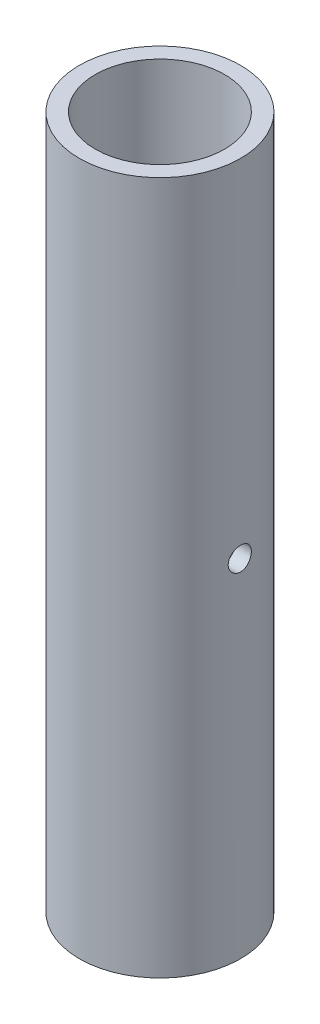
SolidWorks part; units mm, degrees
material "PVC Rigid"
ref_plane "Front Plane" through (0, 0, 0) normal (0, 0, 1) x (1, 0, 0)
ref_plane "Top Plane" through (0, 0, 0) normal (0, 1, 0) x (1, 0, 0)
ref_plane "Right Plane" through (0, 0, 0) normal (1, 0, 0) x (0, 0, -1)
sketch "Sketch2" plane through (0, 0, 0) normal (0, 1, 0) x (1, 0, 0)
  circle A0 centre (0, 0) radius 17.45
  circle A1 centre (0, 0) radius 14
  dimension "D1" = 28
  dimension "D2" = 34.9
extrude "Boss-Extrude1" add sketch "Sketch2" against normal blind 150
ref_plane "Plane1" through (17.45, 0, 0) normal (1, 0, 0) x (0, 0, -1)
hole_wizard "Tap Drill for M6x1.0 Tap1" positions "Sketch3" profile "Sketch4" hole size "M6x1.0" standard "ANSI Metric" end condition through all
sketch "Sketch3" plane through (17.45, 0, 0) normal (1, 0, 0) x (0, 0, -1)
  line L0 (14, 0) -> (-14, 0) construction
  line L1 (-17.45, 0) -> (-17.45, -150) construction
  point P0 (0, -75)
  dimension "D1" = 75
  dimension "D2" = 17.45
sketch "Sketch4" plane through (17.45, -75, 0) normal (0, 1, 0) x (0, 0, -1)
  line L0 (0, 0) -> (0, 34.9)
  line L1 (0, 34.9) -> (2.5, 34.9)
  line L2 (2.5, 34.9) -> (2.5, 0)
  line L5 (2.5, 0) -> (0, 0)
  line L11 (0, -6.35) -> (0, 107.95) construction
  dimension "Thru Hole Dia." = 5
  dimension "Thru Hole Depth" = 34.9
